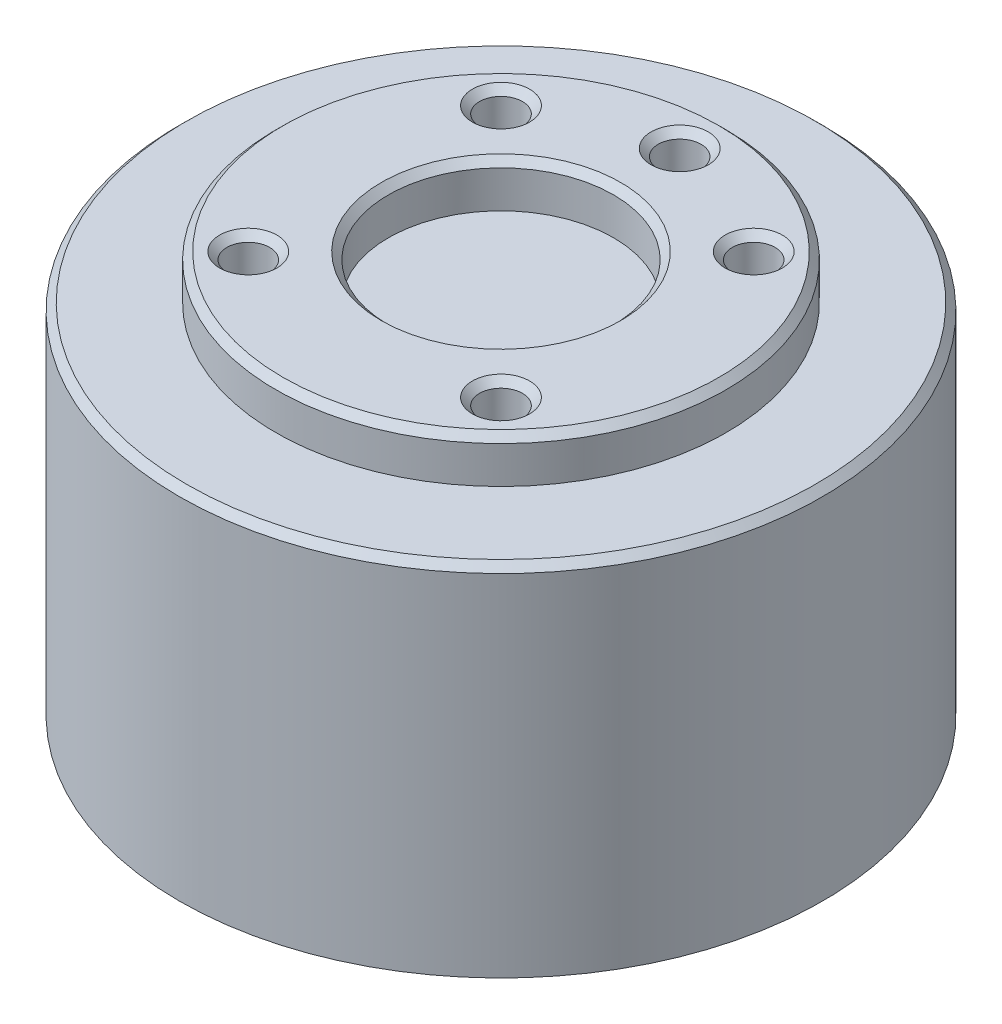
SolidWorks part; units mm, degrees
material "6061-T6 (SS)"
ref_plane "Ebene vorne" through (0, 0, 0) normal (0, 0, 1) x (1, 0, 0)
ref_plane "Ebene oben" through (0, 0, 0) normal (0, 1, 0) x (1, 0, 0)
ref_plane "Ebene rechts" through (0, 0, 0) normal (1, 0, 0) x (0, 0, -1)
sketch "Skizze1" plane through (0, 0, 0) normal (0, 1, 0) x (1, 0, 0)
  circle A0 centre (0, 0) radius 45
  dimension "D1" = 90
extrude "Aufsatz-Linear austragen1" add sketch "Skizze1" along normal blind 50
sketch "Skizze2" plane through (0, 50, 0) normal (0, 1, 0) x (1, 0, 0)
  line L0 (0, 0) -> (17.6777, 17.6777) construction
  line L1 (0, 0) -> (0, 25) construction
  circle A0 centre (0, 0) radius 31.5
  circle A1 centre (0, 0) radius 15.75
  circle A2 centre (17.6777, 17.6777) radius 3
  circle A3 centre (0, 25) radius 3
  circle A4 centre (17.6777, -17.6777) radius 3
  circle A5 centre (-17.6777, -17.6777) radius 3
  circle A6 centre (-17.6777, 17.6777) radius 3
  point P17 (0, 0)
  dimension "D1" = 63
  dimension "D2" = 31.5
  dimension "D5" = 6
  dimension "D6" = 6
  dimension "D3" = 45
  dimension "D4" = 25
  dimension "D7" = 25
  dimension "D8" = 4
extrude "Aufsatz-Linear austragen2" add sketch "Skizze2" along normal blind 6.2
chamfer "Fase1" distance 1 angle 45 8 edges at (-17.6777, 56.2, -14.6777) (17.6777, 56.2, 20.6777) (17.6777, 56.2, -14.6777) (0, 56.2, 31.5) (0, 56.2, 15.75) (0, 56.2, -22) (-17.6777, 56.2, 20.6777) (0, 50, 45)
